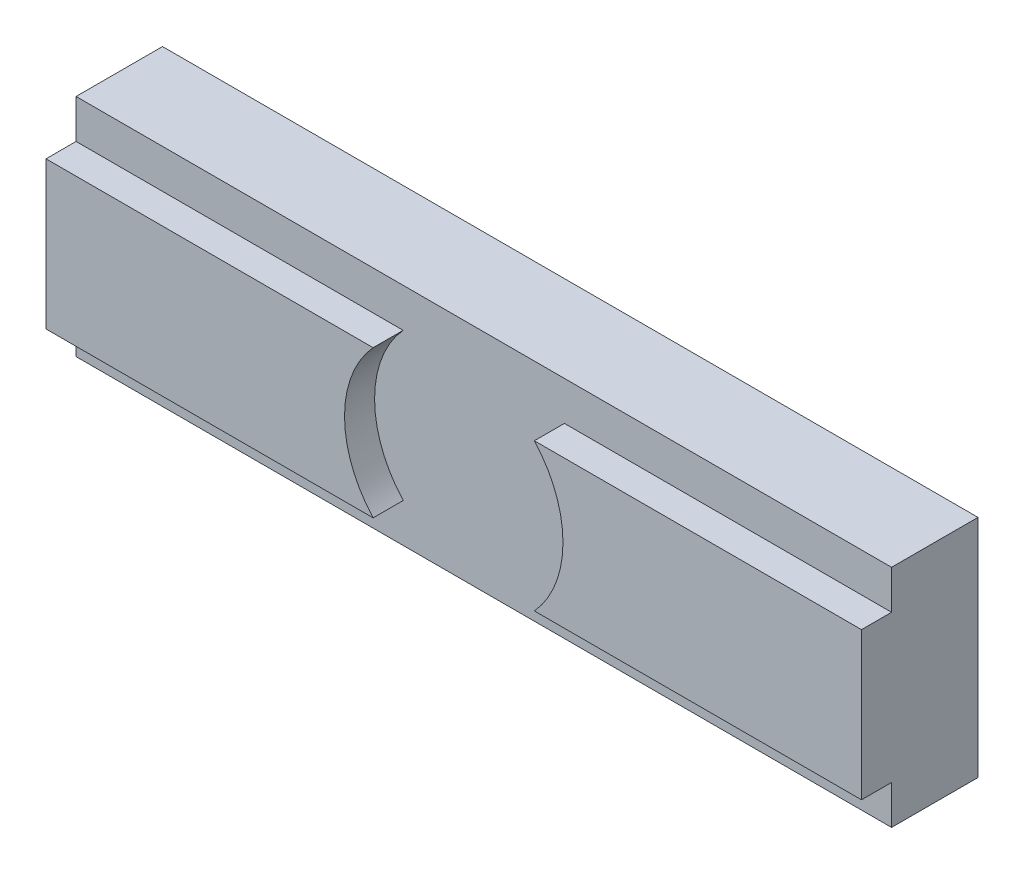
SolidWorks part; units mm, degrees
ref_plane "Front Plane" through (0, 0, 0) normal (0, 0, 1) x (1, 0, 0)
ref_plane "Top Plane" through (0, 0, 0) normal (0, 1, 0) x (1, 0, 0)
ref_plane "Right Plane" through (0, 0, 0) normal (1, 0, 0) x (0, 0, -1)
sketch "Sketch1" plane through (0, 0, 0) normal (1, 0, 0) x (0, 0, -1)
  line L0 (-10, 12.6506) -> (-4.84, 12.6506)
  line L1 (-10, -19.34) -> (10, -19.34)
  line L2 (-10, -19.34) -> (-10, 19.34)
  line L3 (-10, 19.34) -> (10, 19.34)
  line L4 (10, -19.34) -> (10, 19.34)
  line L5 (-10, -19.34) -> (10, 19.34) construction
  line L6 (-10, 19.34) -> (10, -19.34) construction
  line L7 (-4.84, 12.6506) -> (-4.84, 19.34)
  line L9 (55, 0) -> (-55, 0) construction
  line L10 (-10, -12.6506) -> (-4.84, -12.6506)
  line L11 (-4.84, -12.6506) -> (-4.84, -19.34)
  point P0 (0, 0)
  dimension "D1" = 20
  dimension "D2" = 38.68
  dimension "D3" = 6.6894
  dimension "D4" = 5.16
extrude "Boss-Extrude1" add sketch "Sketch1" along normal blind 140 contours L7 L0 L2 L1 L4 L3
sketch "Sketch2" plane through (0, 0, 10) normal (0, 0, 1) x (1, 0, 0)
  line L0 (140, -12.6506) -> (140, 12.6506) construction
  line L1 (140, 42.5) -> (0, 42.5) construction
  circle A0 centre (70, 0) radius 18.75
  dimension "D1" = 37.5
  dimension "D3" = 42.5
  dimension "D2" = 70
extrude "Cut-Extrude1" cut sketch "Sketch2" against normal up to surface (5.16 mm away) up to face at (70, 15.9953, 4.84)
